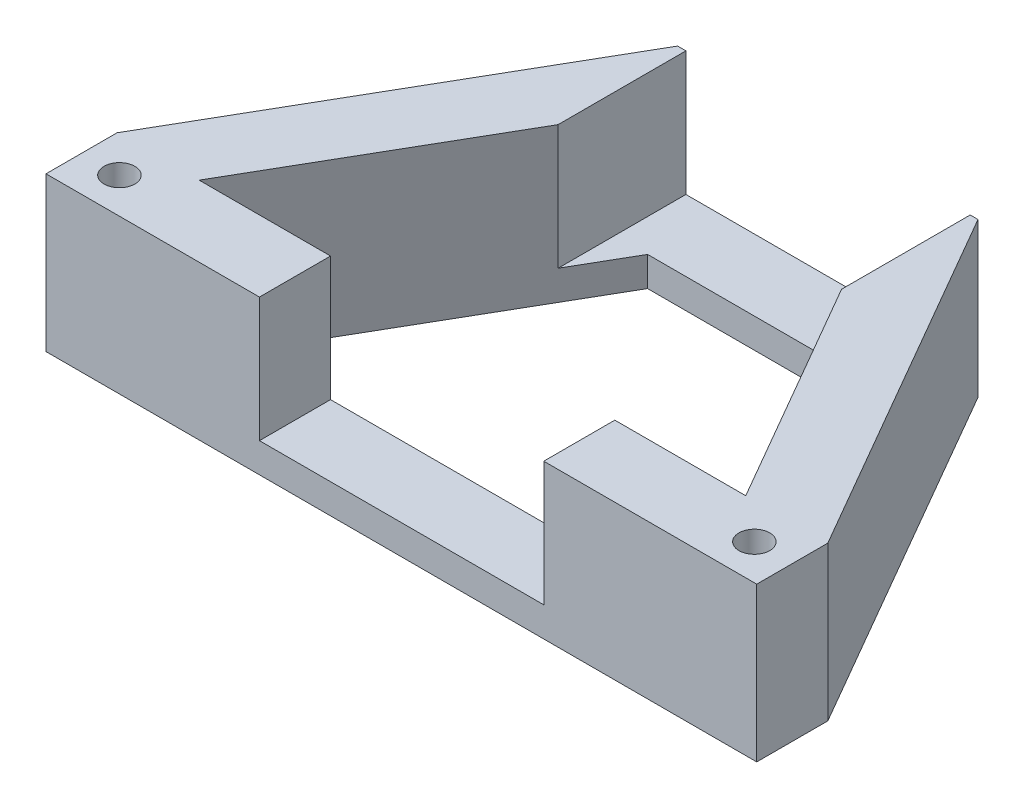
SolidWorks part; units mm, degrees
ref_plane "Front Plane" through (0, 0, 0) normal (0, 0, 1) x (1, 0, 0)
ref_plane "Top Plane" through (0, 0, 0) normal (0, 1, 0) x (1, 0, 0)
ref_plane "Right Plane" through (0, 0, 0) normal (1, 0, 0) x (0, 0, -1)
sketch "Sketch1" plane through (0, 0, 0) normal (0, 1, 0) x (1, 0, 0)
  line L0 (-26.7666, -7.4894) -> (-4.7696, 30.6106)
  line L1 (-17.9678, -7.4894) -> (40.6346, -7.4894)
  line L2 (-26.7666, -7.4894) -> (-26.7666, -15.1094)
  line L3 (-26.7666, -15.1094) -> (49.4334, -15.1094)
  line L4 (49.4334, -7.4894) -> (49.4334, -15.1094)
  line L5 (-4.7696, 30.6106) -> (27.4364, 30.6106)
  line L6 (27.4364, 30.6106) -> (49.4334, -7.4894)
  line L7 (-17.9678, -7.4894) -> (-0.3701, 22.9906)
  line L8 (-0.3701, 22.9906) -> (23.0369, 22.9906)
  line L9 (23.0369, 22.9906) -> (40.6346, -7.4894)
  dimension "D1" = 76.2
  dimension "D2" = 7.62
  dimension "D3" = 38.1
  dimension "D4" = 60
  dimension "D5" = 60
  dimension "D6" = 7.62
  dimension "D7" = 7.62
  dimension "D8" = 7.62
extrude "Boss-Extrude1" add sketch "Sketch1" along normal blind 16.51
sketch "Sketch2" plane through (0, 16.51, 0) normal (0, 1, 0) x (1, 0, 0)
  line L0 (-26.7666, -7.4894) -> (-26.7666, -15.1094) construction
  line L1 (-26.7666, -15.1094) -> (49.4334, -15.1094) construction
  circle A0 centre (-22.7026, -11.2994) radius 1.651
  circle A1 centre (45.3694, -11.2994) radius 1.651
  dimension "D1" = 3.302
  dimension "D5" = 3.302
  dimension "D2" = 3.81
  dimension "D3" = 68.072
  dimension "D4" = 4.064
  dimension "D6" = 3.81
extrude "Cut-Extrude1" cut sketch "Sketch2" against normal blind 16.51
sketch "Sketch3" plane through (0, 16.51, 0) normal (0, 1, 0) x (1, 0, 0)
  line L0 (27.4364, 30.6106) -> (-4.7696, 30.6106) construction
  line L1 (-3.8806, 30.6106) -> (26.5994, 30.6106)
  line L2 (-3.8806, 30.6106) -> (-3.8806, -15.1094)
  line L3 (-3.8806, -15.1094) -> (26.5994, -15.1094)
  line L4 (26.5994, 30.6106) -> (26.5994, -15.1094)
  line L5 (-26.7666, -15.1094) -> (49.4334, -15.1094) construction
  point P11 (11.3594, 30.6106)
  dimension "D1" = 16.129
  dimension "D2" = 30.48
extrude "Cut-Extrude2" cut sketch "Sketch3" against normal blind 13.335
equation "\"hole diameter\"= 0.13"
equation "\"height\"= 0.65"
equation "\"D1@Boss-Extrude1\"=\"height\""
equation "\"D1@Sketch2\"=\"hole diameter\""
equation "\"t\"= 0.3"
equation "\"D2@Sketch1\"=\"t\""
equation "\"D6@Sketch1\"=\"t\""
equation "\"D7@Sketch1\"=\"t\""
equation "\"D8@Sketch1\"=\"t\""
equation "\"D5@Sketch2\"=\"hole diameter\""
